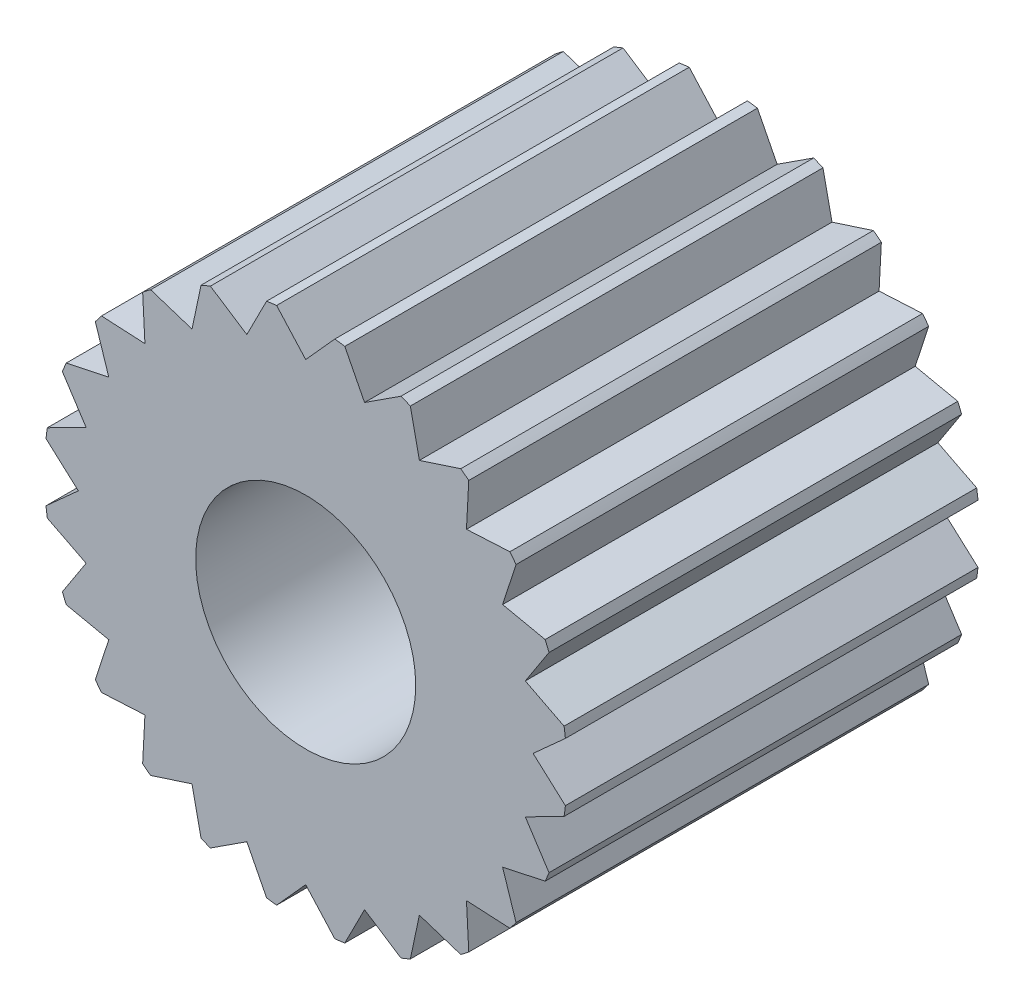
SolidWorks part; units mm, degrees
ref_plane "Plano frontal" through (0, 0, 0) normal (0, 0, 1) x (1, 0, 0)
ref_plane "Plano superior" through (0, 0, 0) normal (0, 1, 0) x (1, 0, 0)
ref_plane "Plano direito" through (0, 0, 0) normal (1, 0, 0) x (0, 0, -1)
sketch "Esboço1" plane through (0, 0, 0) normal (0, 0, 1) x (1, 0, 0)
  circle A0 centre (0, 0) radius 1.9
  circle A1 centre (0, 0) radius 0.8
extrude "Ressalto-extrusão1" add sketch "Esboço1" along normal blind 3
sketch "Esboço2" plane through (0, 0, 3) normal (0, 0, 1) x (1, 0, 0)
  line L0 (0, 0) -> (0, 3.1051) construction
  line L1 (0, 1.6531) -> (0.225, 1.9031)
  line L2 (0.225, 1.9031) -> (-0.225, 1.9031)
  line L3 (-0.225, 1.9031) -> (0, 1.6531)
  line L4 (0.7099, 1.78) -> (0.2752, 1.8965)
  line L5 (0.2752, 1.8965) -> (0.4279, 1.5968)
  line L6 (0.4279, 1.5968) -> (0.7099, 1.78)
  line L7 (1.1464, 1.5357) -> (0.7567, 1.7607)
  line L8 (0.7567, 1.7607) -> (0.8266, 1.4316)
  line L9 (0.8266, 1.4316) -> (1.1464, 1.5357)
  line L10 (1.5048, 1.1866) -> (1.1866, 1.5048)
  line L11 (1.1866, 1.5048) -> (1.1689, 1.1689)
  line L12 (1.1689, 1.1689) -> (1.5048, 1.1866)
  line L13 (1.7607, 0.7567) -> (1.5357, 1.1464)
  line L14 (1.5357, 1.1464) -> (1.4316, 0.8266)
  line L15 (1.4316, 0.8266) -> (1.7607, 0.7567)
  line L16 (1.8965, 0.2752) -> (1.78, 0.7099)
  line L17 (1.78, 0.7099) -> (1.5968, 0.4279)
  line L18 (1.5968, 0.4279) -> (1.8965, 0.2752)
  line L19 (1.9031, -0.225) -> (1.9031, 0.225)
  line L20 (1.9031, 0.225) -> (1.6531, 0)
  line L21 (1.6531, 0) -> (1.9031, -0.225)
  line L22 (1.78, -0.7099) -> (1.8965, -0.2752)
  line L23 (1.8965, -0.2752) -> (1.5968, -0.4279)
  line L24 (1.5968, -0.4279) -> (1.78, -0.7099)
  line L25 (1.5357, -1.1464) -> (1.7607, -0.7567)
  line L26 (1.7607, -0.7567) -> (1.4316, -0.8266)
  line L27 (1.4316, -0.8266) -> (1.5357, -1.1464)
  line L28 (1.1866, -1.5048) -> (1.5048, -1.1866)
  line L29 (1.5048, -1.1866) -> (1.1689, -1.1689)
  line L30 (1.1689, -1.1689) -> (1.1866, -1.5048)
  line L31 (0.7567, -1.7607) -> (1.1464, -1.5357)
  line L32 (1.1464, -1.5357) -> (0.8266, -1.4316)
  line L33 (0.8266, -1.4316) -> (0.7567, -1.7607)
  line L34 (0.2752, -1.8965) -> (0.7099, -1.78)
  line L35 (0.7099, -1.78) -> (0.4279, -1.5968)
  line L36 (0.4279, -1.5968) -> (0.2752, -1.8965)
  line L37 (-0.225, -1.9031) -> (0.225, -1.9031)
  line L38 (0.225, -1.9031) -> (0, -1.6531)
  line L39 (0, -1.6531) -> (-0.225, -1.9031)
  line L40 (-0.7099, -1.78) -> (-0.2752, -1.8965)
  line L41 (-0.2752, -1.8965) -> (-0.4279, -1.5968)
  line L42 (-0.4279, -1.5968) -> (-0.7099, -1.78)
  line L43 (-1.1464, -1.5357) -> (-0.7567, -1.7607)
  line L44 (-0.7567, -1.7607) -> (-0.8266, -1.4316)
  line L45 (-0.8266, -1.4316) -> (-1.1464, -1.5357)
  line L46 (-1.5048, -1.1866) -> (-1.1866, -1.5048)
  line L47 (-1.1866, -1.5048) -> (-1.1689, -1.1689)
  line L48 (-1.1689, -1.1689) -> (-1.5048, -1.1866)
  line L49 (-1.7607, -0.7567) -> (-1.5357, -1.1464)
  line L50 (-1.5357, -1.1464) -> (-1.4316, -0.8266)
  line L51 (-1.4316, -0.8266) -> (-1.7607, -0.7567)
  line L52 (-1.8965, -0.2752) -> (-1.78, -0.7099)
  line L53 (-1.78, -0.7099) -> (-1.5968, -0.4279)
  line L54 (-1.5968, -0.4279) -> (-1.8965, -0.2752)
  line L55 (-1.9031, 0.225) -> (-1.9031, -0.225)
  line L56 (-1.9031, -0.225) -> (-1.6531, 0)
  line L57 (-1.6531, 0) -> (-1.9031, 0.225)
  line L58 (-1.78, 0.7099) -> (-1.8965, 0.2752)
  line L59 (-1.8965, 0.2752) -> (-1.5968, 0.4279)
  line L60 (-1.5968, 0.4279) -> (-1.78, 0.7099)
  line L61 (-1.5357, 1.1464) -> (-1.7607, 0.7567)
  line L62 (-1.7607, 0.7567) -> (-1.4316, 0.8266)
  line L63 (-1.4316, 0.8266) -> (-1.5357, 1.1464)
  line L64 (-1.1866, 1.5048) -> (-1.5048, 1.1866)
  line L65 (-1.5048, 1.1866) -> (-1.1689, 1.1689)
  line L66 (-1.1689, 1.1689) -> (-1.1866, 1.5048)
  line L67 (-0.7567, 1.7607) -> (-1.1464, 1.5357)
  line L68 (-1.1464, 1.5357) -> (-0.8266, 1.4316)
  line L69 (-0.8266, 1.4316) -> (-0.7567, 1.7607)
  line L70 (-0.2752, 1.8965) -> (-0.7099, 1.78)
  line L71 (-0.7099, 1.78) -> (-0.4279, 1.5968)
  line L72 (-0.4279, 1.5968) -> (-0.2752, 1.8965)
  circle A0 centre (0, 0) radius 1.9 construction
  circle A1 centre (0, 0) radius 1.9
  point P79 (0, 0)
  dimension "D1" = 0.25
  dimension "D2" = 0.45
  dimension "D3" = 0.225
  dimension "D4" = 24
extrude "Corte-extrusão2" cut sketch "Esboço2" against normal through all contours L62 L63 L1 | L65 L66 L1 | L68 L69 L1 | L71 L72 L1 | L3 L0 A1 | L0 L1 | L5 L6 L1 | L59 L60 L1 | L56 L57 L1 | L53 L54 L1 | L50 L51 L1 | L47 L48 L1 | L41 L42 L1 | L38 L39 L1 | L35 L36 L1 | L32 L33 L1 | L29 L30 L1 | L26 L27 L1 | L23 L24 L1 | L20 L21 L1 | L17 L18 L1 | L14 L15 L1 | L11 L12 L1 | L8 L9 L1 | L45 L43 L44
